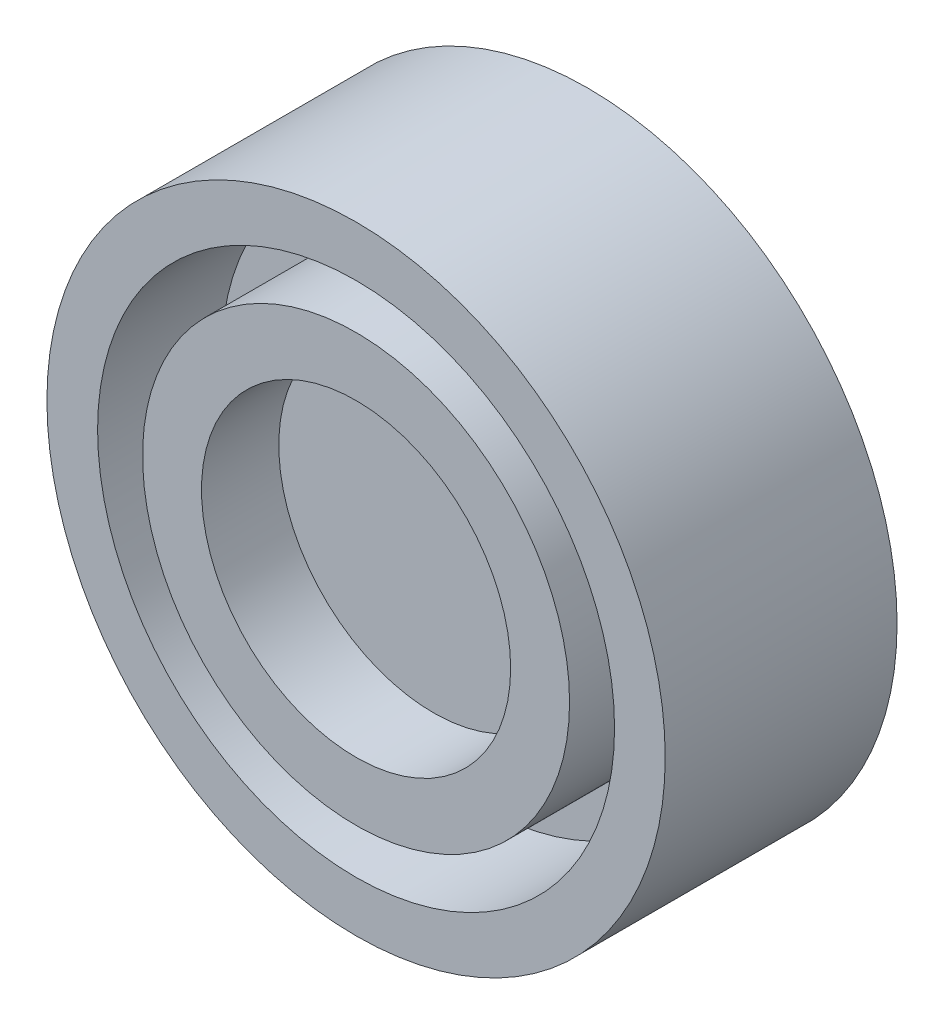
SolidWorks part; units mm, degrees
material "PE High Density"
ref_plane "Front" through (0, 0, 0) normal (0, 0, 1) x (1, 0, 0)
ref_plane "Top" through (0, 0, 0) normal (0, 1, 0) x (1, 0, 0)
ref_plane "Right" through (0, 0, 0) normal (1, 0, 0) x (0, 0, -1)
sketch "Sketch1" plane through (0, 0, 0) normal (0, 0, 1) x (1, 0, 0)
  circle A0 centre (0, 0) radius 20
extrude "Boss-Extrude1" add sketch "Sketch1" along normal blind 15
sketch "Sketch2" plane through (0, 0, 15) normal (0, 0, 1) x (1, 0, 0)
  circle A0 centre (0, 0) radius 10
  circle A1 centre (0, 0) radius 13.3481
  circle A2 centre (0, 0) radius 16.4603
extrude "Cut-Extrude1" cut sketch "Sketch2" against normal blind 5 contours A0
sketch "Sketch3" plane through (0, 0, 15) normal (0, 0, 1) x (1, 0, 0)
  circle A0 centre (0, 0) radius 13.8116
  circle A1 centre (0, 0) radius 16.7223
extrude "Cut-Extrude2" cut sketch "Sketch3" against normal blind 8
